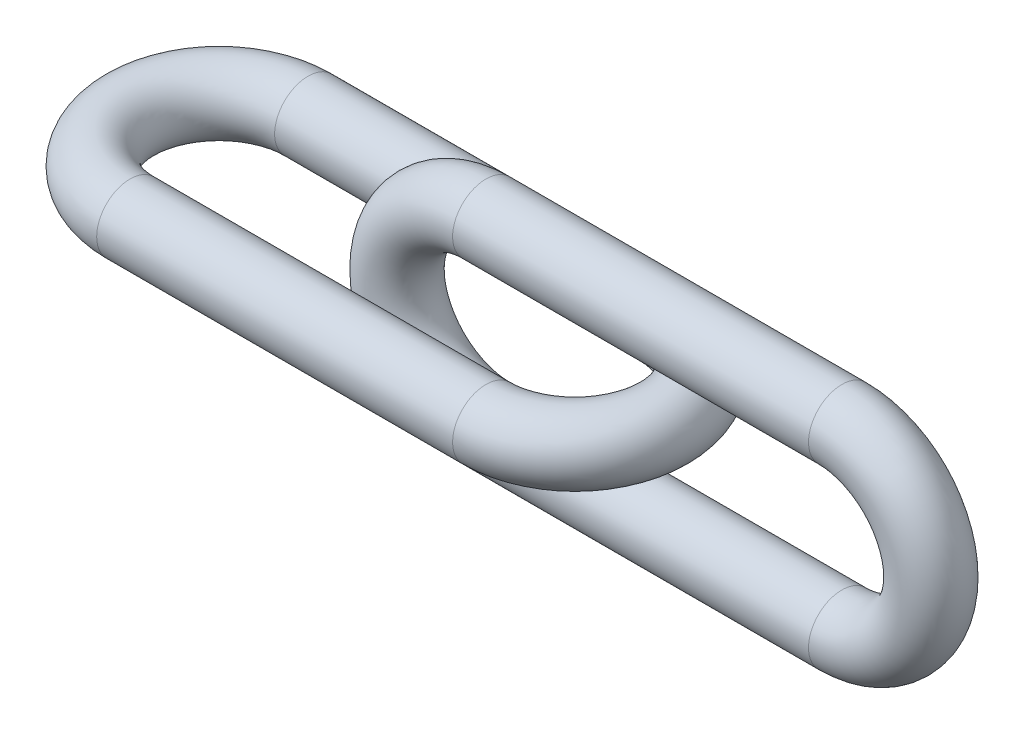
SolidWorks part; units mm, degrees
ref_plane "Front Plane" through (0, 0, 0) normal (0, 0, 1) x (1, 0, 0)
ref_plane "Top Plane" through (0, 0, 0) normal (0, 1, 0) x (1, 0, 0)
ref_plane "Right Plane" through (0, 0, 0) normal (1, 0, 0) x (0, 0, -1)
sketch "Sketch1" plane through (0, 0, 0) normal (0, 0, 1) x (1, 0, 0)
  line L0 (0, 0) -> (40, 0) construction
  line L1 (0, 10) -> (40, 10)
  line L2 (0, -10) -> (40, -10)
  arc A0 (0, 10) -> (0, -10) centre (0, 0) ccw
  arc A1 (40, -10) -> (40, 10) centre (40, 0) ccw
  point P3 (20, 0)
  point P8 (0, 0)
sketch "Sketch12" plane through (0, 0, 0) normal (0, 1, 0) x (1, 0, 0)
  line L0 (-30, 0) -> (10, 0) construction
  line L1 (-30, 10) -> (10, 10)
  line L2 (-30, -10) -> (10, -10)
  arc A0 (-30, 10) -> (-30, -10) centre (-30, 0) ccw
  arc A1 (10, -10) -> (10, 10) centre (10, 0) ccw
  point P2 (-10, 0)
sweep "Sweep4" add path "Sketch1" circular profile diameter 7.5 parameters "D3"=7.5
sweep "Sweep5" add path "Sketch12" circular profile diameter 7.5 parameters "D3"=7.5
